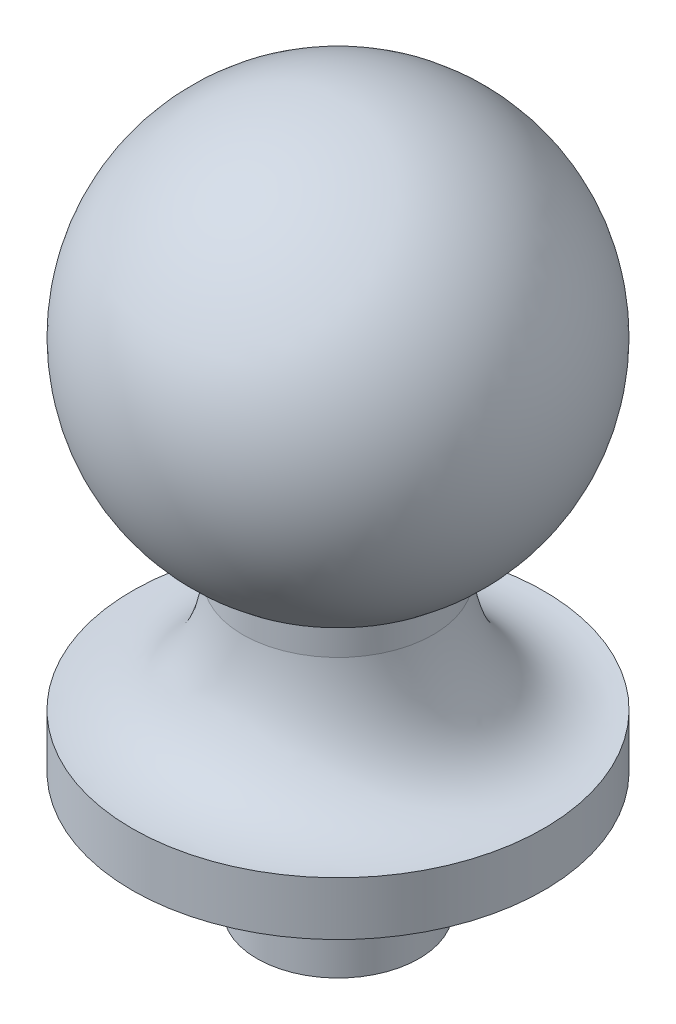
SolidWorks part; units mm, degrees
ref_plane "Front Plane" through (0, 0, 0) normal (0, 0, 1) x (1, 0, 0)
ref_plane "Top Plane" through (0, 0, 0) normal (0, 1, 0) x (1, 0, 0)
ref_plane "Right Plane" through (0, 0, 0) normal (1, 0, 0) x (0, 0, -1)
sketch "Sketch1" plane through (0, 0, 0) normal (1, 0, 0) x (0, 0, -1)
  line L0 (0, 38.956) -> (0, -39.2057) construction
  line L1 (0, 25.4) -> (0, -25.4)
  line L2 (-11.7541, -22.5167) -> (-11.7541, -25.954)
  line L3 (-25.4, -39.8463) -> (-25.4, -46.4531)
  line L4 (-25.4, -46.4531) -> (0, -46.4531)
  line L5 (0, -46.4531) -> (0, -25.4)
  line L6 (-10, -46.4531) -> (-10, -61.4531)
  line L7 (-10, -61.4531) -> (0, -61.4531)
  line L8 (0, -61.4531) -> (0, -46.4531)
  arc A0 (0, 25.4) -> (0, -25.4) centre (0, 0) ccw
  spline S0 degree 2 poles (-11.7541, -25.954) (-13.6251, -40.6638) (-25.4, -39.8463) knots 0 0 0 1 1 1
  dimension "D1" = 50.8
  dimension "D2" = 25.4
  dimension "D3" = 10
  dimension "D4" = 15
revolve "Revolve2" add sketch "Sketch1" angle 360 about L0
ref_plane "Right P" through (0, 0, 0) normal (1, 0, 0) x (0, 0, -1)
ref_plane "Front P" through (0, 0, 0) normal (0, 0, 1) x (1, 0, 0)
